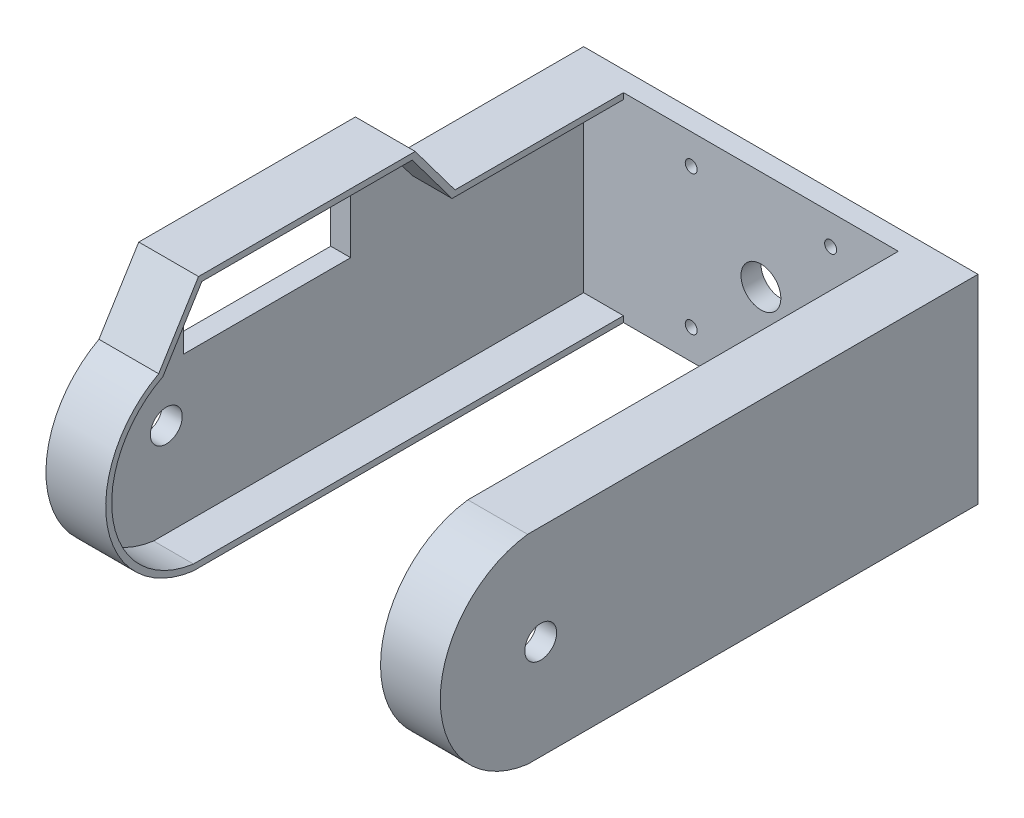
SolidWorks part; units mm, degrees
ref_plane "Front Plane" through (0, 0, 0) normal (0, 0, 1) x (1, 0, 0)
ref_plane "Top Plane" through (0, 0, 0) normal (0, 1, 0) x (1, 0, 0)
ref_plane "Right Plane" through (0, 0, 0) normal (1, 0, 0) x (0, 0, -1)
sketch "Sketch1" plane through (0, 0, 0) normal (0, 0, 1) x (1, 0, 0)
  line L1 (-49.5, 25) -> (49.5, 25)
  line L2 (-49.5, 25) -> (-49.5, -25)
  line L3 (-49.5, -25) -> (49.5, -25)
  line L4 (49.5, 25) -> (49.5, -25)
  dimension "D1" = 49.5
  dimension "D2" = 99
  dimension "D3" = 25
  dimension "D4" = 50
extrude "Boss-Extrude1" add sketch "Sketch1" along normal blind 5
sketch "Sketch2" plane through (0, 0, 5) normal (0, 0, 1) x (1, 0, 0)
  line L0 (-49.5, -25) -> (49.5, -25) construction
  line L1 (49.5, 25) -> (44.5, 25)
  line L2 (49.5, 25) -> (49.5, -25)
  line L3 (49.5, -25) -> (44.5, -25)
  line L4 (44.5, 25) -> (44.5, -25)
  line L6 (-49.5, 25) -> (-44.5, 25)
  line L7 (-49.5, 25) -> (-49.5, -25)
  line L8 (-49.5, -25) -> (-44.5, -25)
  line L9 (-44.5, 25) -> (-44.5, -25)
  dimension "D1" = 5
  dimension "D2" = 5
extrude "Boss-Extrude2" add sketch "Sketch2" along normal blind 130
sketch "Sketch3" plane through (49.5, 0, 0) normal (1, 0, 0) x (0, 0, -1)
  line L0 (-135, -25) -> (-135, 25) construction
  line L5 (0, -25) -> (0, 25)
  line L6 (0, 25) -> (-135, 25)
  line L7 (-135, 25) -> (-135, -25)
  line L8 (-135, -25) -> (0, -25)
  line L9 (0, -25) -> (0, 25)
  line L10 (0, 25) -> (-106.5, 25)
  line L12 (-106.5, -25) -> (0, -25)
  arc A0 (-106.5, 25) -> (-106.5, -25) centre (-109.7851, 0) ccw
  circle A1 centre (-109.7851, 0) radius 4
  dimension "D1" = 0
extrude "Cut-Extrude1" cut sketch "Sketch3" against normal through all flip side to cut
sketch "Sketch5" plane through (0, 0, 0) normal (0, 0, -1) x (-1, 0, 0)
  circle A0 centre (17.5, 17.5) radius 1.5
  circle A1 centre (17.5, -17.5) radius 1.5
  circle A2 centre (-17.5, -17.5) radius 1.5
  circle A3 centre (-17.5, 17.5) radius 1.5
  dimension "D1" = 3
  dimension "D2" = 3
  dimension "D3" = 3
  dimension "D5" = 3
  dimension "D7" = 35
  dimension "D9" = 35
  dimension "D11" = 3
  dimension "D12" = 35
  dimension "D13" = 35
sketch "Sketch7" plane through (49.5, 0, 0) normal (1, 0, 0) x (0, 0, -1)
  line L3 (-113.0702, -25) -> (0, -25)
  line L4 (0, -25) -> (0, 25)
  line L5 (0, 25) -> (-113.0702, 25)
  line L6 (-113.0702, -25) -> (0, -25)
  line L7 (0, -25) -> (0, 25)
  line L8 (0, 25) -> (-113.0702, 25)
  arc A1 (-113.0702, 25) -> (-113.0702, -25) centre (-109.7851, 0) ccw
  arc A2 (-113.0702, 25) -> (-113.0702, -25) centre (-109.7851, 0) ccw
  dimension "D1" = 0
extrude "Extrude-Thin2" add sketch "Sketch7" against normal blind 15 thin thin type one direction reverse wall 1.5
sketch "Sketch8" plane through (-49.5, 0, 0) normal (-1, 0, 0) x (0, 0, 1)
  line L0 (64.5, 34.365) -> (104.5, 34.365) construction
  line L1 (63, 35.365) -> (105.9552, 35.365)
  line L2 (63, 35.365) -> (63, 13.365)
  line L3 (63, 13.365) -> (105.9552, 13.365)
  line L4 (105.9552, 35.365) -> (105.9552, 13.365)
  line L5 (64, 14.865) -> (64, 33.865) construction
  line L6 (104.9552, 14.865) -> (104.9552, 33.865) construction
  dimension "D1" = 1
  dimension "D2" = 1
  dimension "D3" = 22
  dimension "D4" = 1
extrude "Cut-Extrude3" cut sketch "Sketch8" against normal up to next
sketch "Sketch9" plane through (-49.5, 0, 0) normal (-1, 0, 0) x (0, 0, 1)
  line L0 (111.7, 38.365) -> (121.7, 22.2222)
  line L3 (105.4552, 38.365) -> (111.7, 38.365)
  line L5 (121.7, 22.2222) -> (105.9552, 25)
  line L6 (57.3, 38.365) -> (47.3, 25)
  line L7 (63, 25) -> (59.7484, 25)
  line L9 (63.5, 38.365) -> (57.3, 38.365)
  line L11 (63, 25) -> (0, 25) construction
  line L12 (47.3, 25) -> (59.7484, 25)
  line L13 (63, 13.365) -> (105.9552, 13.365) construction
  line L15 (105.9552, 25) -> (105.9552, 13.365)
  line L16 (105.9552, 13.365) -> (105.4552, 13.365)
  line L17 (105.4552, 35.3201) -> (105.4552, 13.365)
  line L20 (63, 25) -> (63, 13.365)
  line L21 (63, 13.365) -> (63.5, 13.365)
  line L22 (63.5, 35.3201) -> (63.5, 13.365)
  line L23 (104.5, 34.3201) -> (64.5, 34.3201) construction
  line L24 (57.3, 20.7719) -> (57.3, 27.958) construction
  line L25 (57.3, 30.5719) -> (57.3, 33.165) construction
  line L26 (111.7, 30.5719) -> (111.7, 33.165) construction
  line L27 (111.7, 20.7719) -> (111.7, 27.958) construction
  line L28 (64.5, 34.365) -> (104.5, 34.365) construction
  line L29 (63.5, 38.365) -> (105.4552, 38.365)
  line L31 (63.5, 35.3201) -> (105.4552, 35.3201)
  arc A0 (113.0702, -25) -> (113.0702, 25) centre (109.7851, 0) ccw construction
  line M18 (113.0702, 25) -> (105.9552, 25)
  line M19 (105.9552, 25) -> (105.9552, 13.365)
  line M20 (105.9552, 13.365) -> (63, 13.365)
  line M21 (63, 13.365) -> (63, 25)
  line M22 (63, 25) -> (0, 25)
  arc M25 (113.0702, -25) -> (113.0702, 25) centre (109.7851, 0) ccw
  dimension "D1" = 0.5
  dimension "D2" = 10
  dimension "D3" = 0.5
  dimension "D4" = 10
  dimension "D5" = 4
  dimension "D6" = 1
extrude "Boss-Extrude4" add sketch "Sketch9" against normal blind 5 contours L22 L31 L17 L0 L3 L29 L9 L6 L21 M20 M19 M18 M25 M22 M21
sketch "Sketch12" plane through (-49.5, 0, 0) normal (-1, 0, 0) x (0, 0, 1)
  line L6 (57.3, 38.365) -> (47.3, 25)
  line L7 (47.3, 25) -> (0, 25)
  line L8 (0, 25) -> (0, -25)
  line L9 (0, -25) -> (113.0702, -25)
  line L10 (121.7, 22.2222) -> (111.7, 38.365)
  line L11 (111.7, 38.365) -> (57.3, 38.365)
  line L12 (57.3, 38.365) -> (47.3, 25)
  line L13 (47.3, 25) -> (0, 25)
  line L14 (0, 25) -> (0, -25)
  line L15 (0, -25) -> (113.0702, -25)
  line L16 (121.7, 22.2222) -> (111.7, 38.365)
  line L17 (111.7, 38.365) -> (57.3, 38.365)
  arc A1 (113.0702, -25) -> (121.7, 22.2222) centre (109.7851, 0) ccw
  arc A2 (113.0702, -25) -> (121.7, 22.2222) centre (109.7851, 0) ccw
  dimension "D1" = 0
extrude "Extrude-Thin3" add sketch "Sketch12" against normal blind 15 thin thin type one direction reverse wall 1.5
sketch "Sketch13" plane through (0, 0, 0) normal (0, 0, -1) x (-1, 0, 0)
  circle A0 centre (0, 0) radius 5
extrude "Cut-Extrude5" cut sketch "Sketch13" against normal up to next
extrude "Cut-Extrude6" cut sketch "Sketch5" against normal through all
